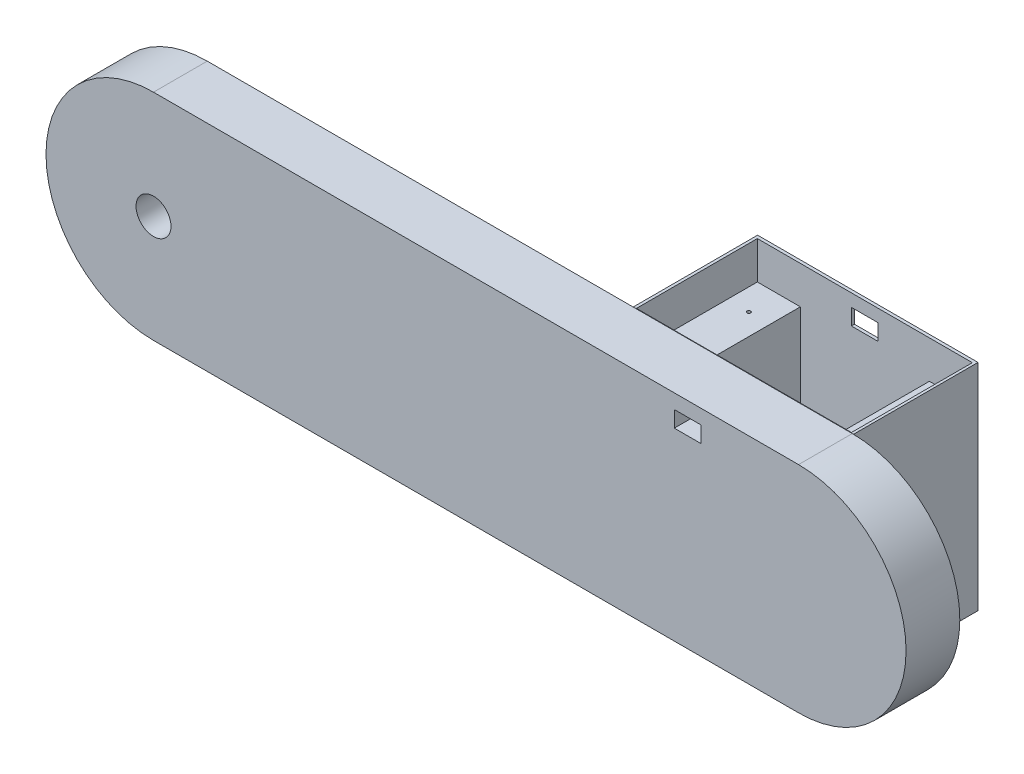
SolidWorks part; units mm, degrees
ref_plane "Front Plane" through (0, 0, 0) normal (0, 0, 1) x (1, 0, 0)
ref_plane "Top Plane" through (0, 0, 0) normal (0, 1, 0) x (1, 0, 0)
ref_plane "Right Plane" through (0, 0, 0) normal (1, 0, 0) x (0, 0, -1)
sketch "Sketch1" plane through (0, 0, 0) normal (0, 0, 1) x (1, 0, 0)
  line L0 (-69.9374, -1.4541) -> (50.0626, -1.4541) construction
  line L5 (-69.9374, 18.5459) -> (50.0626, 18.5459)
  line L6 (-69.9374, -21.4541) -> (50.0626, -21.4541)
  arc A0 (-69.9374, 18.5459) -> (-69.9374, -21.4541) centre (-69.9374, -1.4541) ccw
  arc A1 (50.0626, -21.4541) -> (50.0626, 18.5459) centre (50.0626, -1.4541) ccw
  point P6 (-9.9374, -1.4541)
  dimension "D1" = 40
extrude "Boss-Extrude1" add sketch "Sketch1" along normal blind 10
sketch "Sketch2" plane through (0, 0, 10) normal (0, 0, 1) x (1, 0, 0)
  circle A0 centre (-69.9374, -1.4541) radius 3.25
  dimension "D1" = 6.5
extrude "Cut-Extrude1" cut sketch "Sketch2" against normal blind 6
sketch "Sketch3" plane through (0, 0, 0) normal (0, 0, -1) x (-1, 0, 0)
  line L1 (-49.9445, 18.2003) -> (-8.9445, 18.2003)
  line L2 (-49.9445, 18.2003) -> (-49.9445, -21.7997)
  line L3 (-49.9445, -21.7997) -> (-8.9445, -21.7997)
  line L4 (-8.9445, 18.2003) -> (-8.9445, -21.7997)
  dimension "D1" = 40
  dimension "D2" = 41
extrude "Boss-Extrude2" add sketch "Sketch3" along normal blind 23.5
sketch "Sketch6" plane through (0, 18.2003, 0) normal (0, 1, 0) x (1, 0, 0)
  line L1 (9.4653, 22.9318) -> (49.4653, 22.9318)
  line L2 (9.4653, 22.9318) -> (9.4653, 0.4318)
  line L3 (9.4653, 0.4318) -> (49.4653, 0.4318)
  line L4 (49.4653, 22.9318) -> (49.4653, 0.4318)
  dimension "D1" = 40
  dimension "D2" = 22.5
extrude "Cut-Extrude3" cut sketch "Sketch6" against normal blind 39
sketch "Sketch7" plane through (0, -20.7997, 0) normal (0, 1, 0) x (1, 0, 0)
  line L0 (9.4653, 0.4318) -> (49.4653, 0.4318) construction
  line L1 (9.4653, 22.9318) -> (17.4653, 22.9318)
  line L2 (9.4653, 22.9318) -> (9.4653, 0.4318)
  line L3 (9.4653, 0.4318) -> (17.4653, 0.4318)
  line L4 (17.4653, 22.9318) -> (17.4653, 0.4318)
  line L6 (49.4653, 22.9318) -> (41.4653, 22.9318)
  line L7 (49.4653, 22.9318) -> (49.4653, 0.4318)
  line L8 (49.4653, 0.4318) -> (41.4653, 0.4318)
  line L9 (41.4653, 22.9318) -> (41.4653, 0.4318)
  dimension "D1" = 8
  dimension "D2" = 8
extrude "Boss-Extrude3" add sketch "Sketch7" along normal blind 32
sketch "Sketch8" plane through (0, 11.2003, 0) normal (0, 1, 0) x (1, 0, 0)
  line L0 (9.4653, 11.6818) -> (49.4653, 11.6818) construction
  line L1 (9.4653, 22.9318) -> (9.4653, 0.4318) construction
  line L2 (49.4653, 0.4318) -> (49.4653, 22.9318) construction
  line L3 (9.4653, 11.6818) -> (49.4653, 22.9318) construction
  line L4 (9.4653, 17.3068) -> (49.4653, 17.3068) construction
  line L5 (9.4653, 11.6818) -> (49.4653, 0.4318) construction
  line L6 (9.4653, 6.0568) -> (49.4653, 6.0568) construction
  line L7 (49.4653, 0.4318) -> (49.4653, 22.9318) construction
  circle A0 centre (45.4881, 17.3068) radius 0.325
  circle A1 centre (45.4881, 6.0568) radius 0.325
  circle A2 centre (13.5053, 17.3068) radius 0.325
  circle A3 centre (13.5053, 6.0568) radius 0.325
  dimension "D1" = 0.65
  dimension "D2" = 0.65
  dimension "D3" = 0.65
  dimension "D4" = 0.65
extrude "Cut-Extrude4" cut sketch "Sketch8" against normal blind 6
sketch "Sketch9" plane through (0, 0, -23.5) normal (0, 0, -1) x (-1, 0, 0)
  line L0 (-29.4445, 18.2003) -> (-29.4445, -21.7997) construction
  line L1 (-8.9445, 18.2003) -> (-49.9445, 18.2003) construction
  line L2 (-49.9445, -21.7997) -> (-8.9445, -21.7997) construction
  line L3 (-49.9445, 14.3608) -> (-8.9445, 14.3608) construction
  line L4 (-49.9445, 18.2003) -> (-49.9445, -21.7997) construction
  line L5 (-8.9445, -21.4541) -> (-8.9445, 18.2003) construction
  line L7 (-31.9407, 15.8626) -> (-26.9483, 15.8626)
  line L8 (-31.9407, 15.8626) -> (-31.9407, 12.859)
  line L9 (-31.9407, 12.859) -> (-26.9483, 12.859)
  line L10 (-26.9483, 15.8626) -> (-26.9483, 12.859)
  line L11 (-31.9407, 15.8626) -> (-26.9483, 12.859) construction
  line L12 (-31.9407, 12.859) -> (-26.9483, 15.8626) construction
  point P12 (-29.4445, 14.3608)
extrude "Cut-Extrude5" cut sketch "Sketch9" against normal blind 55
